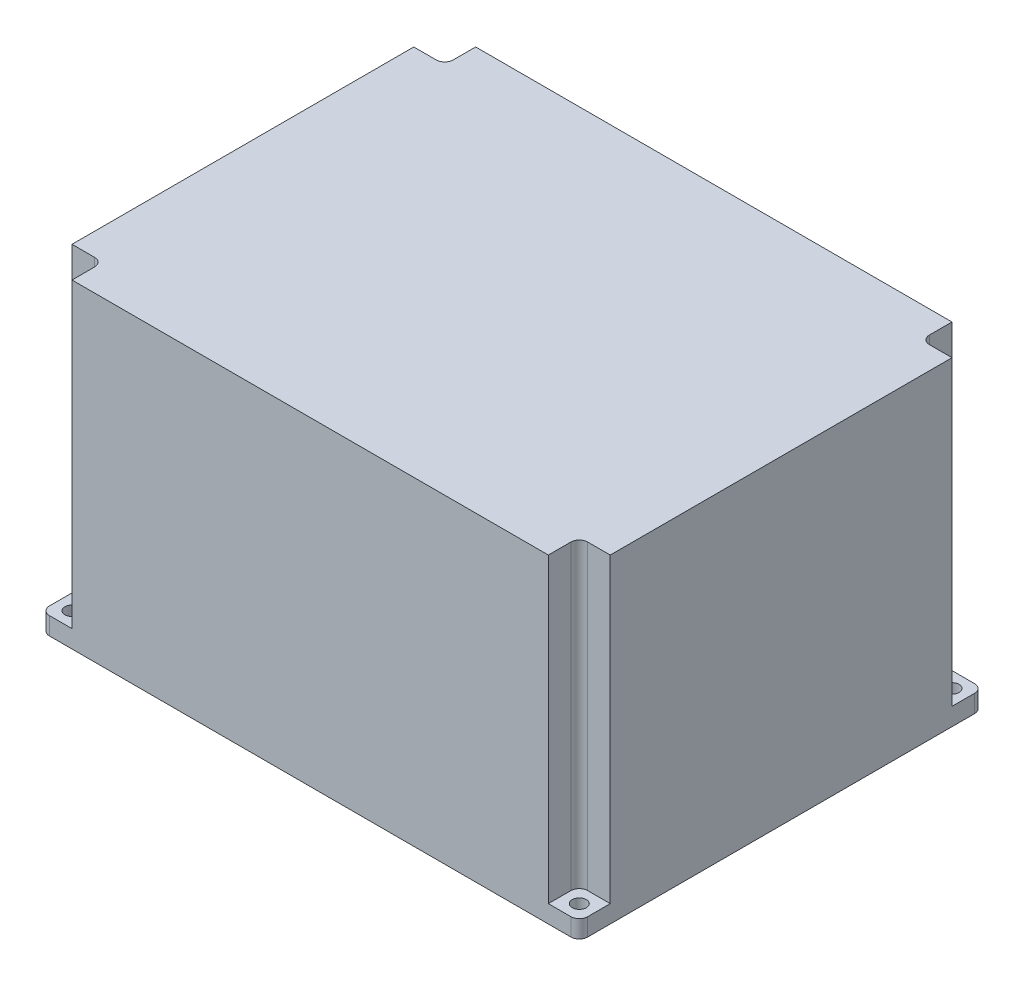
SolidWorks part; units mm, degrees
ref_plane "Front" through (0, 0, 0) normal (0, 0, 1) x (1, 0, 0)
ref_plane "Top" through (0, 0, 0) normal (0, 1, 0) x (1, 0, 0)
ref_plane "Right" through (0, 0, 0) normal (1, 0, 0) x (0, 0, -1)
sketch "Szkic1" plane through (0, 0, 0) normal (0, 1, 0) x (1, 0, 0)
  line L1 (-103.974, 70.578) -> (51.026, 70.578)
  line L2 (-106.474, 68.078) -> (-106.474, -46.922)
  line L3 (-103.974, -49.422) -> (51.026, -49.422)
  line L4 (53.526, 68.078) -> (53.526, -46.922)
  arc A0 (51.026, -49.422) -> (53.526, -46.922) centre (51.026, -46.922) ccw
  arc A1 (-103.974, -49.422) -> (-106.474, -46.922) centre (-103.974, -46.922) cw
  arc A2 (-106.474, 68.078) -> (-103.974, 70.578) centre (-103.974, 68.078) cw
  arc A3 (53.526, 68.078) -> (51.026, 70.578) centre (51.026, 68.078) ccw
  point P8 (-106.474, -49.422)
  point P11 (-106.474, 70.578)
  point P14 (53.526, 70.578)
  dimension "D3" = 2.5
  dimension "D1" = 120
  dimension "D2" = 160
extrude "Dodanie-wyciągnięcie1" add sketch "Szkic1" along normal blind 95
sketch "Szkic3" plane through (0, 95, 0) normal (0, 1, 0) x (1, 0, 0)
  line L0 (51.026, 70.578) -> (63.7564, 70.578) construction
  line L1 (53.526, 68.078) -> (53.526, 77.1907) construction
  line L2 (53.526, 70.578) -> (53.526, 61.378)
  line L7 (53.526, -46.922) -> (53.526, 68.078) construction
  line L8 (53.526, 70.578) -> (44.326, 70.578)
  line L9 (51.026, 70.578) -> (-103.974, 70.578) construction
  line L10 (53.526, 61.378) -> (46.826, 61.378)
  line L11 (44.326, 63.878) -> (44.326, 70.578)
  line L12 (-26.474, 70.578) -> (-26.474, -49.422) construction
  line L13 (-103.974, -49.422) -> (51.026, -49.422) construction
  line L14 (-106.474, 10.578) -> (53.526, 10.578) construction
  line L15 (-106.474, 68.078) -> (-106.474, -46.922) construction
  line L16 (-106.474, 68.078) -> (-106.474, 77.1907) construction
  line L17 (-103.974, 70.578) -> (-116.7044, 70.578) construction
  line L18 (-97.274, 63.878) -> (-97.274, 70.578)
  line L19 (-106.474, 61.378) -> (-99.774, 61.378)
  line L20 (-106.474, 70.578) -> (-97.274, 70.578)
  line L21 (-106.474, 70.578) -> (-106.474, 61.378)
  line L22 (-103.974, -49.422) -> (-116.7044, -49.422) construction
  line L23 (-106.474, -46.922) -> (-106.474, -56.0346) construction
  line L24 (-106.474, -49.422) -> (-106.474, -40.222)
  line L25 (-106.474, -49.422) -> (-97.274, -49.422)
  line L26 (-106.474, -40.222) -> (-99.774, -40.222)
  line L27 (-97.274, -42.722) -> (-97.274, -49.422)
  line L28 (53.526, -46.922) -> (53.526, -56.0346) construction
  line L29 (51.026, -49.422) -> (63.7564, -49.422) construction
  line L30 (44.326, -42.722) -> (44.326, -49.422)
  line L31 (53.526, -40.222) -> (46.826, -40.222)
  line L32 (53.526, -49.422) -> (44.326, -49.422)
  line L33 (53.526, -49.422) -> (53.526, -40.222)
  arc A0 (46.826, 61.378) -> (44.326, 63.878) centre (46.826, 63.878) cw
  arc A1 (-99.774, 61.378) -> (-97.274, 63.878) centre (-99.774, 63.878) ccw
  arc A2 (-99.774, -40.222) -> (-97.274, -42.722) centre (-99.774, -42.722) cw
  arc A3 (46.826, -40.222) -> (44.326, -42.722) centre (46.826, -42.722) ccw
  dimension "D3" = 2.5
  dimension "D1" = 9.2
  dimension "D2" = 9.2
extrude "Wytnij-wyciągnięcie2" cut sketch "Szkic3" against normal blind 89.75
sketch "Szkic6" plane through (0, 5.25, 0) normal (0, 1, 0) x (1, 0, 0)
  line L0 (53.526, 61.378) -> (44.326, 70.578) construction
  line L1 (44.326, 70.578) -> (-97.274, 70.578) construction
  line L2 (-26.474, 70.578) -> (-26.474, -82.4763) construction
  line L3 (-106.474, 61.378) -> (-106.474, -40.222) construction
  line L4 (-106.474, 10.578) -> (159.3609, 10.578) construction
  line L5 (-106.474, 61.378) -> (-97.274, 70.578) construction
  line L6 (-106.474, -40.222) -> (-97.274, -49.422) construction
  line L7 (44.326, -49.422) -> (-97.274, -49.422) construction
  line L8 (53.526, -40.222) -> (44.326, -49.422) construction
  circle A0 centre (48.926, 65.978) radius 2.1
  circle A1 centre (-101.874, 65.978) radius 2.1
  circle A2 centre (-101.874, -44.822) radius 2.1
  circle A3 centre (48.926, -44.822) radius 2.1
extrude "Wytnij-wyciągnięcie4" cut sketch "Szkic6" against normal up to surface (5.25 mm away) up to face at (-26.474, 0, -10.578)
sketch "Szkic7" plane through (-106.474, 0, 0) normal (-1, 0, 0) x (0, 0, 1)
  line L0 (-100.682, 67) -> (62.8332, 67) construction
  line L1 (-68.078, 0) -> (46.922, 0) construction
  line L8 (-10.578, 0) -> (-10.578, 81.0486) construction
  line L9 (-61.378, 5.25) -> (40.222, 5.25) construction
  line L10 (-58.9081, 61) -> (37.1342, 61) construction
  line L11 (34.422, 84.8673) -> (34.422, -24.2981) construction
  line L12 (-55.578, 84.8673) -> (-55.578, -24.2981) construction
  line L14 (-55.578, 61) -> (34.422, 61)
  line L15 (-55.578, 61) -> (-55.578, 5.25)
  line L16 (-55.578, 5.25) -> (34.422, 5.25)
  line L17 (34.422, 61) -> (34.422, 5.25)
  dimension "D1" = 67
  dimension "D2" = 61
  dimension "D3" = 45
extrude "Wytnij-wyciągnięcie6" cut sketch "Szkic7" against normal blind 1
sketch "Szkic8" plane through (0, 5.25, 0) normal (0, 1, 0) x (1, 0, 0)
  line L0 (-106.474, 61.378) -> (-106.8139, 80.6626) construction
  line L1 (-97.274, 70.578) -> (-106.6361, 70.578) construction
  line L2 (-106.474, -40.222) -> (-106.474, -64.1226) construction
  line L3 (-97.274, -49.422) -> (-106.474, -49.422) construction
  line L4 (-97.274, -49.422) -> (-106.474, -49.422) construction
  line L5 (-101.9551, 70.578) -> (-101.874, -49.422) construction
ref_plane "Płaszczyzna1" through (-101.9073, 0, 0.0688) normal (1, 0, -0.0007) x (-0.0007, 0, -1)
